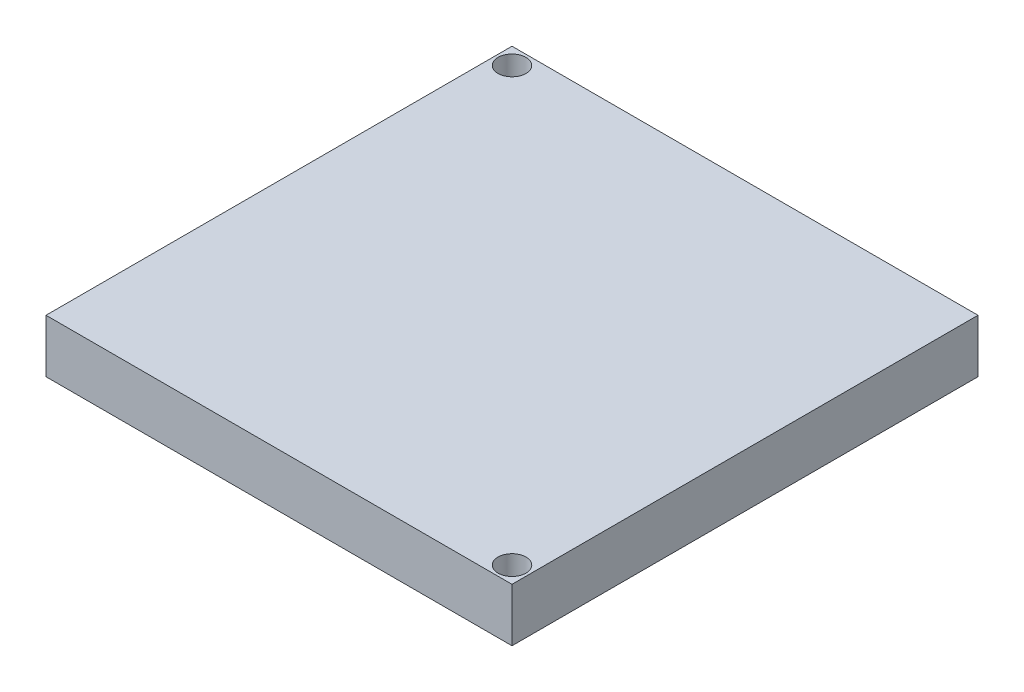
SolidWorks part; units mm, degrees
ref_plane "前视基准面" through (0, 0, 0) normal (0, 0, 1) x (1, 0, 0)
ref_plane "上视基准面" through (0, 0, 0) normal (0, 1, 0) x (1, 0, 0)
ref_plane "右视基准面" through (0, 0, 0) normal (1, 0, 0) x (0, 0, -1)
sketch "草图1" plane through (0, 0, 0) normal (0, 1, 0) x (1, 0, 0)
  line L1 (-35, 35) -> (35, 35)
  line L2 (-35, 35) -> (-35, -35)
  line L3 (-35, -35) -> (35, -35)
  line L4 (35, 35) -> (35, -35)
  line L5 (-35, 35) -> (35, -35) construction
  line L6 (-35, -35) -> (35, 35) construction
  point P0 (0, 0)
  dimension "D1" = 70
  dimension "D2" = 70
extrude "凸台-拉伸1" add sketch "草图1" along normal blind 8
sketch "草图2" plane through (0, 8, 0) normal (0, 1, 0) x (1, 0, 0)
  line L1 (-32.5, 32.5) -> (32.5, 32.5)
  line L2 (-32.5, 32.5) -> (-32.5, -32.5)
  line L3 (-32.5, -32.5) -> (32.5, -32.5)
  line L4 (32.5, 32.5) -> (32.5, -32.5)
  line L5 (-32.5, 32.5) -> (32.5, -32.5) construction
  line L6 (-32.5, -32.5) -> (32.5, 32.5) construction
  circle A0 centre (-32.5, 32.5) radius 2.1
  circle A1 centre (32.5, -32.5) radius 2.1
  point P0 (0, 0)
  dimension "D3" = 4.2
  dimension "D4" = 4.2
  dimension "D1" = 65
  dimension "D2" = 65
extrude "切除-拉伸1" cut sketch "草图2" against normal blind 8 contours A0 | A1
